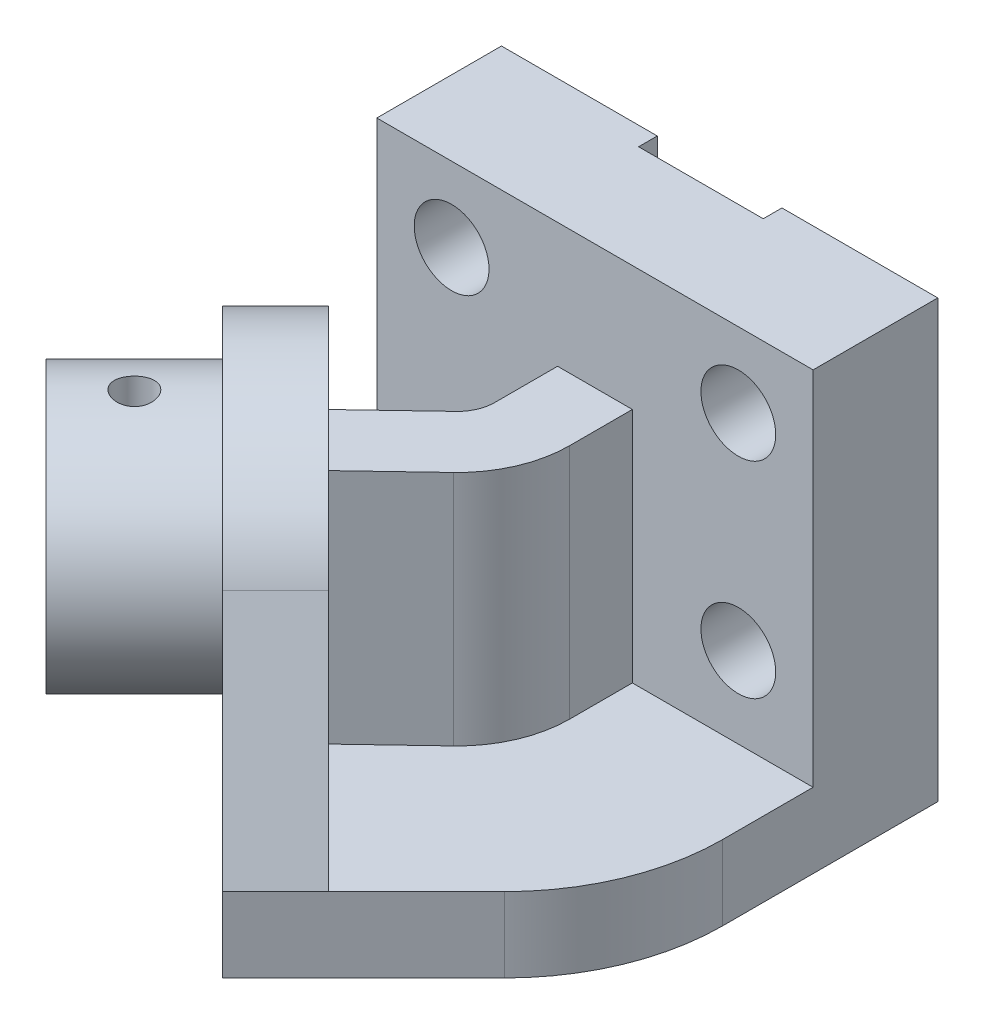
SolidWorks part; units mm, degrees
ref_plane "Front Plane" through (0, 0, 0) normal (0, 0, 1) x (1, 0, 0)
ref_plane "Top Plane" through (0, 0, 0) normal (0, 1, 0) x (1, 0, 0)
ref_plane "Right Plane" through (0, 0, 0) normal (1, 0, 0) x (0, 0, -1)
sketch "Sketch1" plane through (0, 0, 0) normal (0, 1, 0) x (1, 0, 0)
  line L0 (-10, 20) -> (-10, 17)
  line L1 (-35, 20) -> (-10, 20)
  line L2 (-35, 20) -> (-35, 0)
  line L3 (-35, 0) -> (35, 0)
  line L4 (35, 20) -> (35, 0)
  line L5 (-10, 17) -> (10, 17)
  line L6 (10, 17) -> (10, 20)
  line L8 (0, 0) -> (0, 77.8517) construction
  line L9 (10, 20) -> (35, 20)
  point P4 (0, 0)
  dimension "D1" = 70
  dimension "D2" = 20
  dimension "D3" = 20
  dimension "D4" = 3
extrude "Boss-Extrude1" add sketch "Sketch1" against normal mid plane 70
ref_plane "Plane1" through (0, -35, 0) normal (0, -1, 0) x (-1, 0, 0)
sketch "Sketch2" plane through (0, -35, 0) normal (0, -1, 0) x (-1, 0, 0)
  line L5 (-35, 0) -> (35, 0)
  line L6 (35, 0) -> (47.3774, -12.3774)
  line L7 (47.3774, -12.3774) -> (-2.1213, -61.8762)
  line L8 (-2.1213, -61.8762) -> (-24.7487, -39.2487)
  line L9 (-35, -14.5) -> (-35, 0)
  arc A1 (-24.7487, -39.2487) -> (-35, -14.5) centre (0, -14.5) cw
  point P8 (46.1523, -11.1523)
  dimension "D4" = 135
  dimension "D1" = 35
  dimension "D2" = 14.5
  dimension "D3" = 32
extrude "Boss-Extrude2" add sketch "Sketch2" against normal blind 12
sketch "Sketch3" plane through (-29.8774, 0, 29.8774) normal (-0.7071, 0, 0.7071) x (0.7071, 0, 0.7071)
  line L0 (45.253, -35) -> (-24.7487, -35) construction
  line L1 (45.253, -35) -> (-24.7487, -35) construction
  line L2 (10.2522, -35) -> (10.2522, 3) construction
  line L3 (-24.7487, -23) -> (-13.4687, 10.8943)
  line L4 (45.253, -23) -> (33.973, 10.8943)
  line L5 (-24.7487, -23) -> (45.253, -23)
  arc A0 (33.973, 10.8943) -> (-13.4687, 10.8943) centre (10.2522, 3) ccw
  dimension "D1" = 50
  dimension "D2" = 38
extrude "Boss-Extrude3" add sketch "Sketch3" against normal blind 12
sketch "Sketch4" plane through (-29.8774, 0, 29.8774) normal (-0.7071, 0, 0.7071) x (0.7071, 0, 0.7071)
  circle A0 centre (10.2522, 3) radius 19
  dimension "D1" = 38
extrude "Boss-Extrude4" add sketch "Sketch4" along normal blind 20
sketch "Sketch5" plane through (0, -23, 0) normal (0, 1, 0) x (1, 0, 0)
  line L0 (0, 0) -> (0, -20.5551) construction
  line L1 (-6, 0) -> (-6, -10.0636)
  line L2 (-35, 0) -> (35, 0) construction
  line L3 (-7.8696, -14.4156) -> (-18.3869, -24.3974)
  line L4 (2.6304, -45.4147) -> (-30.916, -11.8683) construction
  line L5 (-35, 0) -> (35, 0) construction
  line L6 (-9.8987, -32.8856) -> (-18.3869, -24.3974)
  line L7 (-14.1428, -28.6415) -> (-8.6014, -23.3822) construction
  line L8 (-38.8921, -3.8921) -> (10.6066, -53.3909) construction
  line L9 (6, 0) -> (6, -10.0636)
  line L10 (0.3912, -23.1195) -> (-9.8987, -32.8856)
  line L11 (-6, 0) -> (6, 0)
  arc A0 (-6, -10.0636) -> (-7.8696, -14.4156) centre (-12, -10.0636) cw
  arc A1 (0.3912, -23.1195) -> (6, -10.0636) centre (-12, -10.0636) ccw
  dimension "D1" = 6
  dimension "D3" = 18
  dimension "D2" = 14.5
extrude "Boss-Extrude5" add sketch "Sketch5" along normal blind 38
hole_wizard "Hole1" positions "Sketch6" profile "Sketch7" legacy
sketch "Sketch6" plane through (0, 0, 0) normal (0, 0, 1) x (1, 0, 0)
  line L1 (-45.0319, -35) -> (45.0319, -35) construction
  point P0 (23, -10)
  dimension "D1" = 23
  dimension "D2" = 25
sketch "Sketch7" plane through (23, -10, 0) normal (1, 0, 0) x (0, -1, 0)
  line L0 (0, 0) -> (0, 100)
  line L1 (0, 100) -> (6, 100)
  line L2 (6, 100) -> (6, 0)
  line L3 (6, 0) -> (0, 0)
  line L4 (0, 110) -> (0, -10) construction
  dimension "Diameter" = 12
  dimension "Depth" = 100
pattern_linear "LPattern1" count 2 spacing 33 along (0, 1, 0) of "Hole1"
pattern_linear "LPattern2" count 2 spacing 46 along (-1, 0, 0) of "LPattern1", "Hole1"
sketch "Sketch8" plane through (0, 35, 0) normal (0, 1, 0) x (1, 0, 0)
  line L0 (-14.1428, -28.6415) -> (-45.2555, -59.7542) construction
  line L1 (2.6304, -45.4147) -> (-30.916, -11.8683) construction
  line L2 (-50.2052, -37.8339) -> (-23.3352, -64.704) construction
  circle A0 centre (-29.6991, -44.1979) radius 3
  point P8 (-29.2294, -44.6675)
  point P9 (-14.1428, -90.8669)
  point P10 (-44.9882, -60.0215)
  point P11 (-46.7686, -58.241)
  point P12 (-46.6846, -58.3251)
  point P13 (-46.0962, -58.9135)
  point P14 (-45.4658, -59.5439)
  dimension "D1" = 6
  dimension "D2" = 10
extrude "Cut-Extrude1" cut sketch "Sketch8" against normal through all
